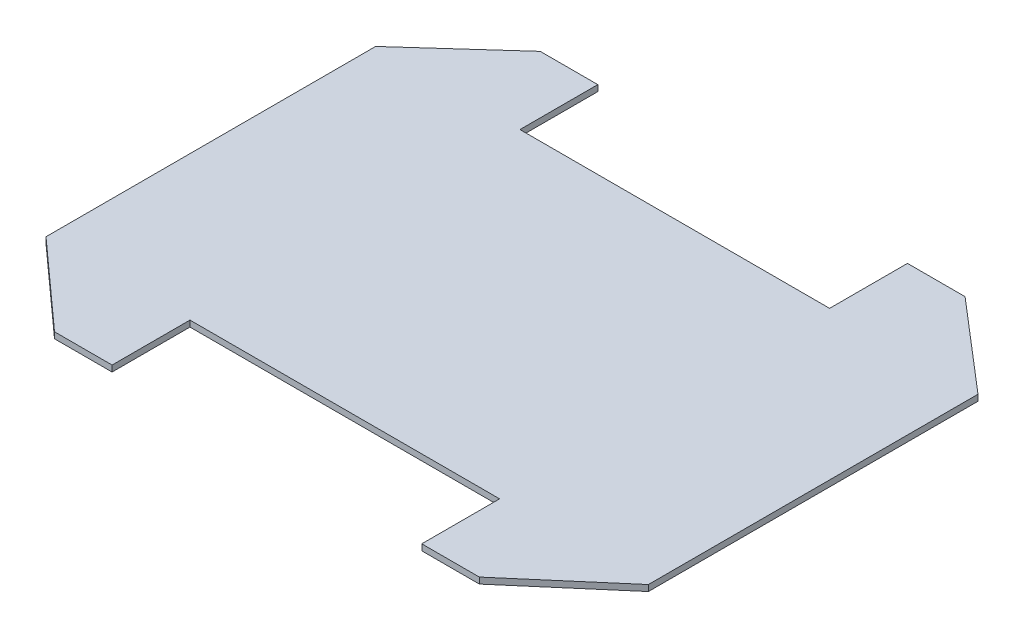
SolidWorks part; units mm, degrees
ref_plane "Спереди" through (0, 0, 0) normal (0, 0, 1) x (1, 0, 0)
ref_plane "Сверху" through (0, 0, 0) normal (0, 1, 0) x (1, 0, 0)
ref_plane "Справа" through (0, 0, 0) normal (1, 0, 0) x (0, 0, -1)
sketch "Эскиз1" plane through (0, 0, 0) normal (0, 1, 0) x (1, 0, 0)
  line L1 (-270.7591, 74.6607) -> (-270.7591, -223.012)
  line L2 (139.0683, -293.4928) -> (191.0683, -293.4928)
  line L3 (-140.5865, 145.1415) -> (-192.5865, 145.1415)
  line L4 (139.0683, -223.1757) -> (139.0683, -293.4928)
  line L5 (139.0683, 145.1415) -> (191.0683, 145.1415)
  line L6 (-140.5865, 74.8243) -> (-140.5865, 145.1415)
  line L7 (-0.7591, -12.2026) -> (-0.7591, 227.1905) construction
  line L8 (273.2409, 74.6607) -> (273.2409, -223.012)
  line L9 (-140.5865, -223.1757) -> (139.0683, -223.1757)
  line L10 (139.0683, 74.8243) -> (139.0683, 145.1415)
  line L11 (-140.5865, 74.8243) -> (139.0683, 74.8243)
  line L12 (-140.5865, -223.1757) -> (-140.5865, -293.4928)
  line L13 (-140.5865, -293.4928) -> (-192.5865, -293.4928)
  line L17 (-326.8393, -74.1757) -> (107.7018, -74.1757) construction
  line L22 (-270.7591, 74.6607) -> (-192.5865, 145.1415)
  line L23 (-270.7591, -223.012) -> (-192.5865, -293.4928)
  line L26 (273.2409, -223.012) -> (191.0683, -293.4928)
  line L27 (273.2409, 74.6607) -> (191.0683, 145.1415)
  dimension "D1" = 149
  dimension "D2" = 149
  dimension "D3" = 274
  dimension "D4" = 270
extrude "Вытянуть1" add sketch "Эскиз1" along normal blind 5.5
